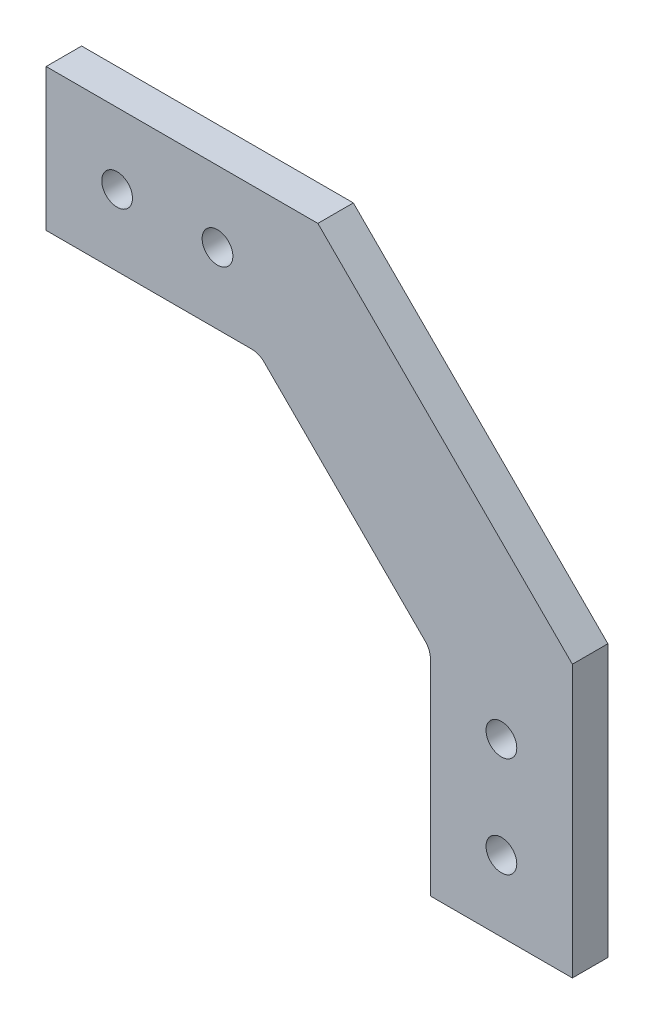
SolidWorks part; units mm, degrees
material "6061-T6 (SS)"
ref_plane "Front" through (0, 0, 0) normal (0, 0, 1) x (1, 0, 0)
ref_plane "Top" through (0, 0, 0) normal (0, 1, 0) x (1, 0, 0)
ref_plane "Right" through (0, 0, 0) normal (1, 0, 0) x (0, 0, -1)
sketch "Sketch4" plane through (-292.1, 0, 0) normal (0, 0, 1) x (1, 0, 0)
  line L0 (292.1, 63.5) -> (292.1, 0)
  line L1 (342.1, 0) -> (242.1, 0) construction
  line L2 (292.1, 63.5) -> (254, 101.6)
  line L4 (254, 101.6) -> (-254, 101.6)
  line L5 (292.1, 0) -> (-292.1, 0) construction
  line L6 (-254, 101.6) -> (-292.1, 63.5)
  line L7 (-292.1, 63.5) -> (-292.1, -25.4)
  dimension "D1" = 90
sketch "Sketch1" plane through (0, 0, 0) normal (0, 0, 1) x (1, 0, 0)
  line L0 (-12.7, 29.0295) -> (-12.7, 58.2395)
  line L6 (-12.7, 58.2395) -> (-43.3605, 88.9)
  line L7 (-43.3605, 88.9) -> (-81.4605, 88.9)
  line L8 (-81.4605, 88.9) -> (-81.4605, 114.3)
  line L9 (-81.4605, 114.3) -> (-32.8395, 114.3)
  line L10 (-32.8395, 114.3) -> (12.7, 68.7605)
  line L11 (12.7, 68.7605) -> (12.7, 37.9195)
  line L12 (-12.7, 29.0295) -> (-12.7, 0) construction
  line L13 (0, 63.5) -> (-38.1, 101.6) construction
  line L14 (-38.1, 101.6) -> (-546.1, 101.6) construction
  line L15 (12.7, 37.9195) -> (-12.7, 37.9195) construction
  line L16 (-12.7, 37.9195) -> (-12.7, 58.2395) construction
  line L17 (12.7, 29.0295) -> (12.7, 20.1395)
  line L18 (12.7, 20.1395) -> (-12.7, 20.1395)
  line L19 (-12.7, 20.1395) -> (-12.7, 29.0295)
  line L20 (12.7, 29.0295) -> (-12.7, 29.0295) construction
  line L21 (12.7, 37.9195) -> (12.7, 29.0295)
  line L22 (0, 20.1395) -> (0, 0) construction
  line L23 (0, 0) -> (-584.2, 0) construction
  point P2 (0, 0)
  point P24 (-12.7, 52.0679)
  dimension "D1" = 25.4
  dimension "D2" = 8.89
  dimension "D3" = 38.1
  dimension "D4" = 8.89
  dimension "D5" = 12.7
  dimension "D6" = 12.7
  dimension "D7" = 12.7
  dimension "D8" = 12.7
  dimension "D9" = 38.1
extrude "Boss-Extrude1" add sketch "Sketch1" along normal blind 6.35
fillet "Fillet1" radius 3.175 2 edges at (-43.3605, 88.9, 3.175) (-12.7, 58.2395, 3.175)
hole_wizard "M5 Clearance Hole1" positions "Sketch2" profile "Sketch3" hole size "M5" standard "ANSI Metric"
sketch "Sketch2" plane through (0, 0, 6.35) normal (0, 0, 1) x (1, 0, 0)
  line L14 (-81.4605, 114.3) -> (-68.7605, 101.6) construction
  line L15 (-68.7605, 101.6) -> (-81.4605, 88.9) construction
  line L17 (-68.7605, 101.6) -> (-50.8, 101.6) construction
  line L22 (12.7, 20.1395) -> (0, 32.8395) construction
  line L23 (0, 32.8395) -> (-12.7, 20.1395) construction
  line L25 (0, 32.8395) -> (0, 50.8) construction
  point P0 (0, 50.8)
  point P48 (-50.8, 101.6)
  point P50 (-68.7605, 101.6)
  point P87 (0, 32.8395)
  point P88 (0, 0)
  point P89 (0, 0)
  dimension "D4" = 12.7
sketch "Sketch3" plane through (0, 50.8, 6.35) normal (1, 0, 0) x (0, -1, 0)
  line L0 (0, 0) -> (0, 20.4024)
  line L1 (0, 20.4024) -> (2.75, 18.75)
  line L2 (2.75, 18.75) -> (2.75, 0)
  line L5 (2.75, 0) -> (0, 0)
  line L10 (0, 20.4024) -> (-2.75, 18.75) construction
  line L11 (0, -6.35) -> (0, 107.95) construction
  dimension "Hole Dia." = 5.5
  dimension "Hole Depth" = 18.75
  dimension "Drill Angle" = 118
